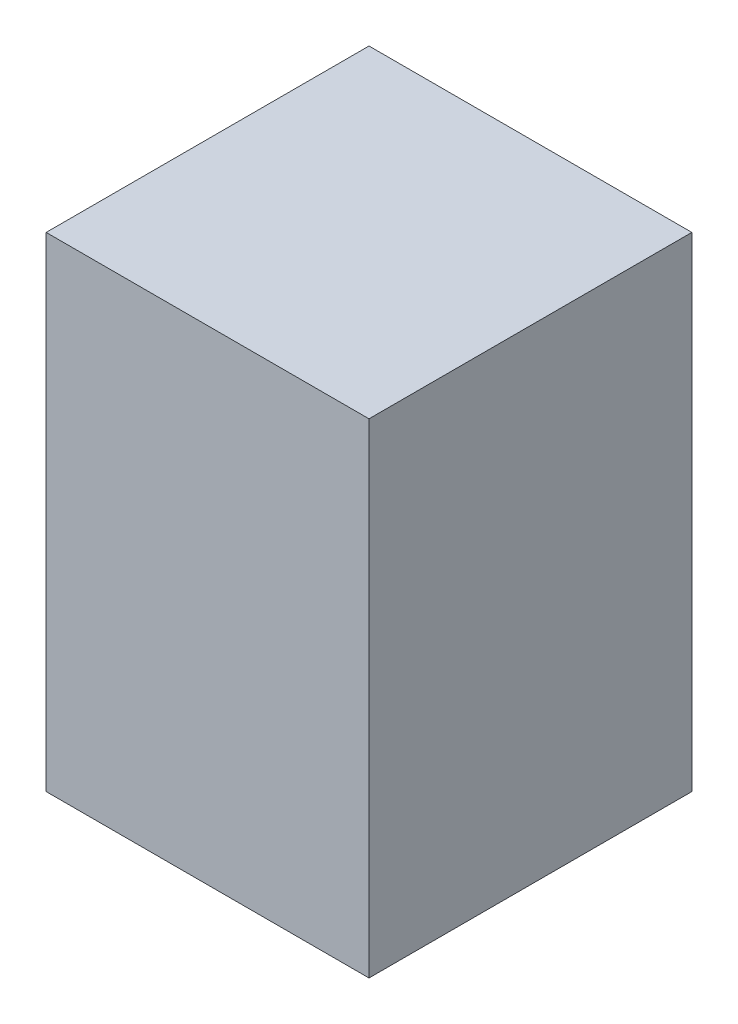
SolidWorks part; units mm, degrees
ref_plane "Front Plane" through (0, 0, 0) normal (0, 0, 1) x (1, 0, 0)
ref_plane "Top Plane" through (0, 0, 0) normal (0, 1, 0) x (1, 0, 0)
ref_plane "Right Plane" through (0, 0, 0) normal (1, 0, 0) x (0, 0, -1)
other "Configuration Table"
sketch "Sketch1" plane through (0, 0, 0) normal (0, 0, 1) x (1, 0, 0)
  line L1 (60, 0) -> (140, 0)
  line L2 (60, 0) -> (60, 120)
  line L3 (60, 120) -> (140, 120)
  line L4 (140, 0) -> (140, 120)
extrude "PRESS_ayak_1_1" add sketch "Sketch1" against normal blind 80 from offset 40 separate body
